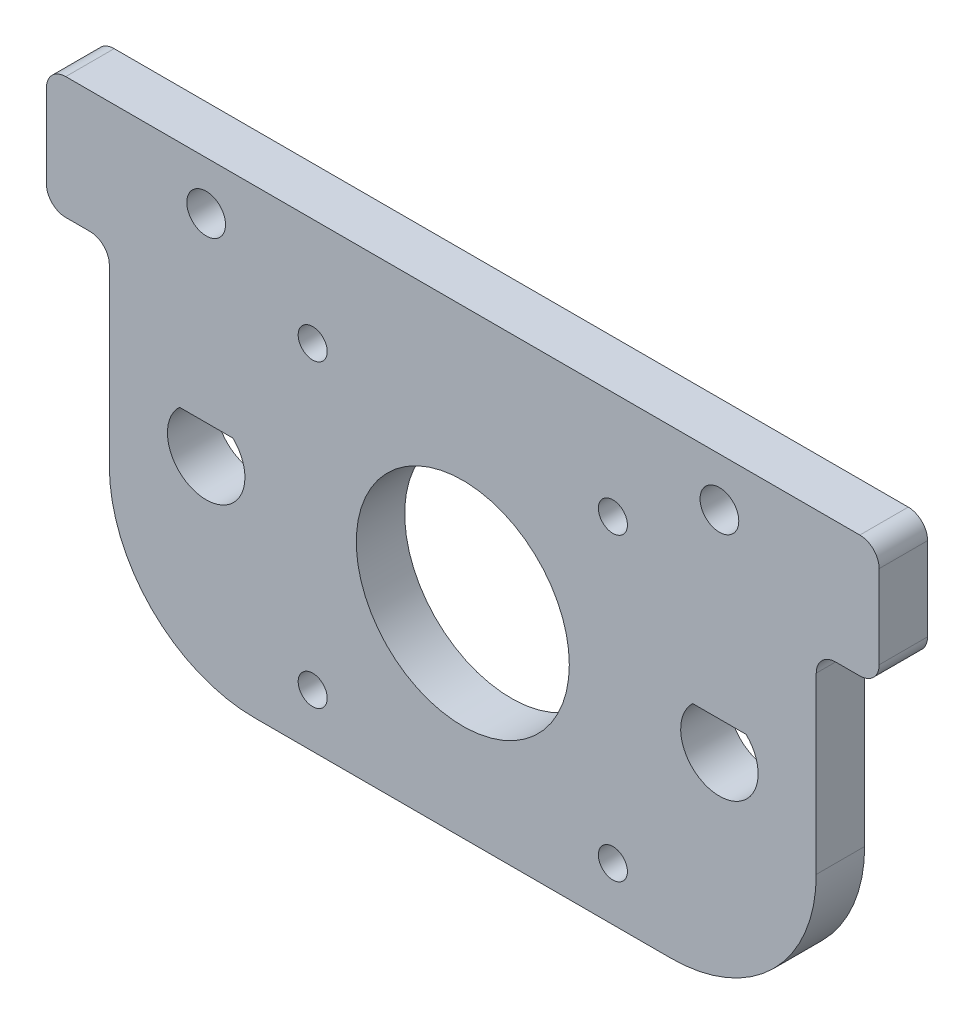
SolidWorks part; units mm, degrees
ref_plane "Front Plane" through (0, 0, 0) normal (0, 0, 1) x (1, 0, 0)
ref_plane "Top Plane" through (0, 0, 0) normal (0, 1, 0) x (1, 0, 0)
ref_plane "Right Plane" through (0, 0, 0) normal (1, 0, 0) x (0, 0, -1)
sketch "Sketch1" plane through (0, 0, 0) normal (0, 0, 1) x (1, 0, 0)
  line L0 (43, 12.6) -> (43, -17.048) construction
  line L1 (0, 0) -> (6.5, 0)
  line L2 (0, 0) -> (0, 12.6)
  line L3 (0, 12.6) -> (86, 12.6)
  line L4 (86, 0) -> (86, 12.6)
  line L5 (13.745, -11.1) -> (19.255, -11.1)
  line L6 (27.5, -29.5) -> (58.5, -29.5) construction
  line L7 (27.5, -29.5) -> (27.5, 1.5) construction
  line L8 (27.5, 1.5) -> (58.5, 1.5) construction
  line L9 (58.5, -29.5) -> (58.5, 1.5) construction
  line L10 (27.5, -29.5) -> (58.5, 1.5) construction
  line L11 (27.5, 1.5) -> (58.5, -29.5) construction
  line L12 (50.5056, -14) -> (46.7528, -7.5) construction
  line L13 (46.7528, -7.5) -> (39.2472, -7.5) construction
  line L14 (39.2472, -7.5) -> (35.4944, -14) construction
  line L15 (35.4944, -14) -> (39.2472, -20.5) construction
  line L16 (39.2472, -20.5) -> (46.7528, -20.5) construction
  line L17 (46.7528, -20.5) -> (50.5056, -14) construction
  line L18 (66.745, -11.1) -> (72.255, -11.1)
  line L19 (6.5, 0) -> (6.5, -35)
  line L20 (6.5, -35) -> (79.5, -35)
  line L21 (79.5, 0) -> (79.5, -35)
  line L22 (79.5, 0) -> (86, 0)
  line L24 (22, -35) -> (64, -35) construction
  line L25 (22, -35) -> (22, 7) construction
  line L26 (22, 7) -> (64, 7) construction
  line L27 (64, -35) -> (64, 7) construction
  line L28 (22, -35) -> (64, 7) construction
  line L29 (22, 7) -> (64, -35) construction
  circle A0 centre (69.5, 7.6) radius 2
  circle A1 centre (16.5, 7.6) radius 2
  circle A2 centre (43, -14) radius 11
  circle A3 centre (43, -14) radius 6.5 construction
  circle A4 centre (27.5, -29.5) radius 1.5
  circle A5 centre (58.5, -29.5) radius 1.5
  circle A6 centre (27.5, 1.5) radius 1.5
  circle A7 centre (58.5, 1.5) radius 1.5
  arc A8 (13.745, -11.1) -> (19.255, -11.1) centre (16.5, -14) ccw
  arc A9 (66.745, -11.1) -> (72.255, -11.1) centre (69.5, -14) ccw
  point P12 (43, -14)
  point P41 (43, -35)
  dimension "D3" = 4
  dimension "D5" = 5
  dimension "D8" = 22
  dimension "D9" = 26.6
  dimension "D11" = 3
  dimension "D12" = 8
  dimension "D13" = 8
  dimension "D1" = 86
  dimension "D2" = 53
  dimension "D4" = 53
  dimension "D6" = 12.6
  dimension "D7" = 31
  dimension "D10" = 13
  dimension "D14" = 2.9
  dimension "D15" = 10
  dimension "D16" = 21
  dimension "D17" = 42
extrude "Boss-Extrude1" add sketch "Sketch1" along normal blind 5
fillet "Fillet1" radius 2 6 edges at (86, 12.6, 2.5) (0, 12.6, 2.5) (6.5, 0, 2.5) (79.5, 0, 2.5) (86, 0, 2.5) (0, 0, 2.5)
fillet "Fillet2" radius 15 2 edges at (79.5, -35, 2.5) (6.5, -35, 2.5)
